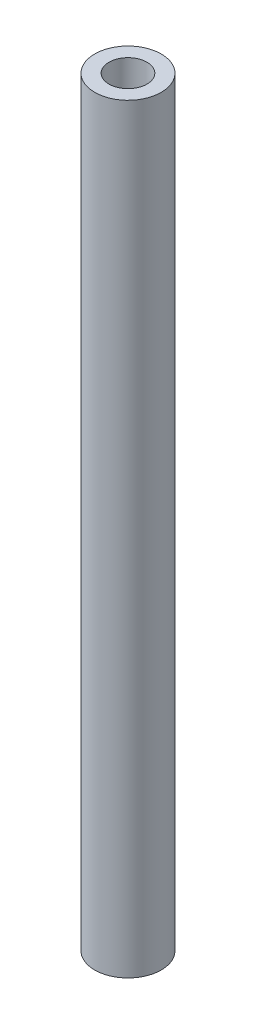
SolidWorks part; units mm, degrees
material "1060 合金"
ref_plane "前视基准面" through (0, 0, 0) normal (0, 0, 1) x (1, 0, 0)
ref_plane "上视基准面" through (0, 0, 0) normal (0, 1, 0) x (1, 0, 0)
ref_plane "右视基准面" through (0, 0, 0) normal (1, 0, 0) x (0, 0, -1)
sketch "草图1" plane through (0, 0, 0) normal (0, 1, 0) x (1, 0, 0)
  circle A0 centre (0, 0) radius 2
  circle A1 centre (0, 0) radius 3.5
  dimension "D1" = 4
  dimension "D2" = 7
extrude "凸台-拉伸1" add sketch "草图1" along normal blind 80
